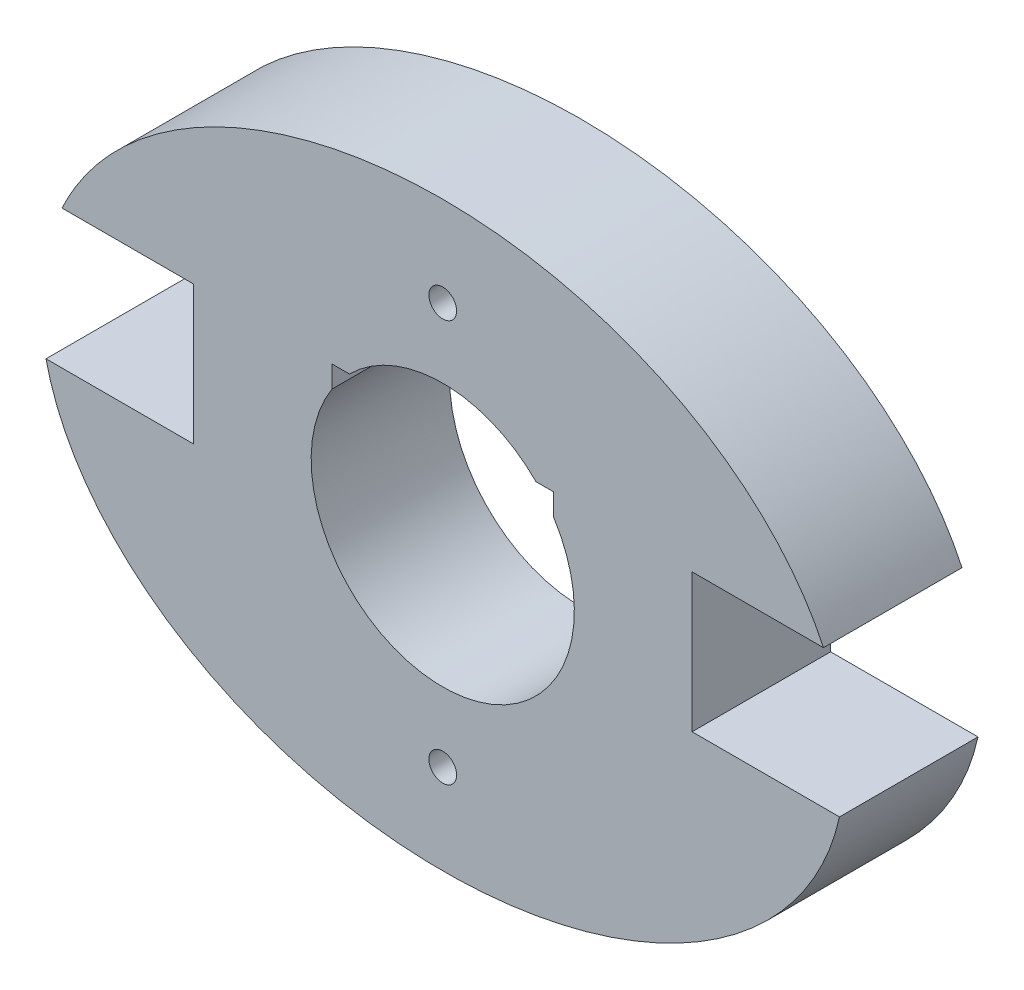
SolidWorks part; units mm, degrees
material "Balsa"
ref_plane "Plan de face" through (0, 0, 0) normal (0, 0, 1) x (1, 0, 0)
ref_plane "Plan de dessus" through (0, 0, 0) normal (0, 1, 0) x (1, 0, 0)
ref_plane "Plan de droite" through (0, 0, 0) normal (1, 0, 0) x (0, 0, -1)
sketch "Esquisse1" plane through (0, 0, 0) normal (0, 0, 1) x (1, 0, 0)
  line L0 (-20.8509, -1.65) -> (20.8509, -1.65) construction
  line L1 (0, 7.2545) -> (0, -7.2545) construction
  line L2 (-14.5, 0) -> (14.5, 0) construction
  line L3 (-20.8509, 3.35) -> (20.8509, 3.35) construction
  line L4 (20.8509, 3.35) -> (-20.8509, -1.65) construction
  line L5 (20.8509, -1.65) -> (-20.8509, 3.35) construction
  line L6 (-13.7422, 3.35) -> (-9, 3.35)
  line L7 (13.7422, 3.35) -> (9, 3.35)
  line L8 (14.3199, -1.65) -> (9, -1.65)
  line L9 (-14.3199, -1.65) -> (-9, -1.65)
  line L10 (-9, 3.35) -> (-9, -1.65)
  line L11 (9, 3.35) -> (9, -1.65)
  line L12 (15.2888, 0.85) -> (-16.9334, 0.85) construction
  circle A5 centre (0, 7.2545) radius 0.5
  circle A6 centre (0, -7.2545) radius 0.5
  circle A9 centre (0, 0) radius 4.75
  ellipse E0 centre (0, 0) end of major axis (14.5, 0) minor radius 10.5 (-13.7422, 3.35) -> (13.7422, 3.35) cw
  ellipse E1 centre (0, 0) end of major axis (14.5, 0) minor radius 10.5 (-14.3199, -1.65) -> (14.3199, -1.65) ccw
  point P1 (0, 0.85)
  dimension "D2" = 9.5
  dimension "D7" = 1
  dimension "D8" = 1
  dimension "D1" = 5
  dimension "D4" = 18
  dimension "D6" = 21
  dimension "D9" = 0.85
  dimension "D10" = 29
extrude "Boss.-Extru.1" add sketch "Esquisse1" along normal blind 5
sketch "Esquisse2" plane through (0, 0, 0) normal (0, 0, -1) x (-1, 0, 0)
  line L0 (-9, 3.35) -> (-13.7422, 3.35) construction
  line L1 (4, 3.35) -> (4, -1.65)
  line L2 (-4, 3.35) -> (-4, -1.65)
  line L3 (4, 3.35) -> (-4, 3.35)
  line L4 (-4, -1.65) -> (4, -1.65)
  line L5 (0, 0) -> (0, 18.2087) construction
  line L6 (-14.3199, -1.65) -> (-9, -1.65) construction
  dimension "D1" = 8
extrude "Enlèv. mat.-Extru.1" cut sketch "Esquisse2" against normal blind 5
